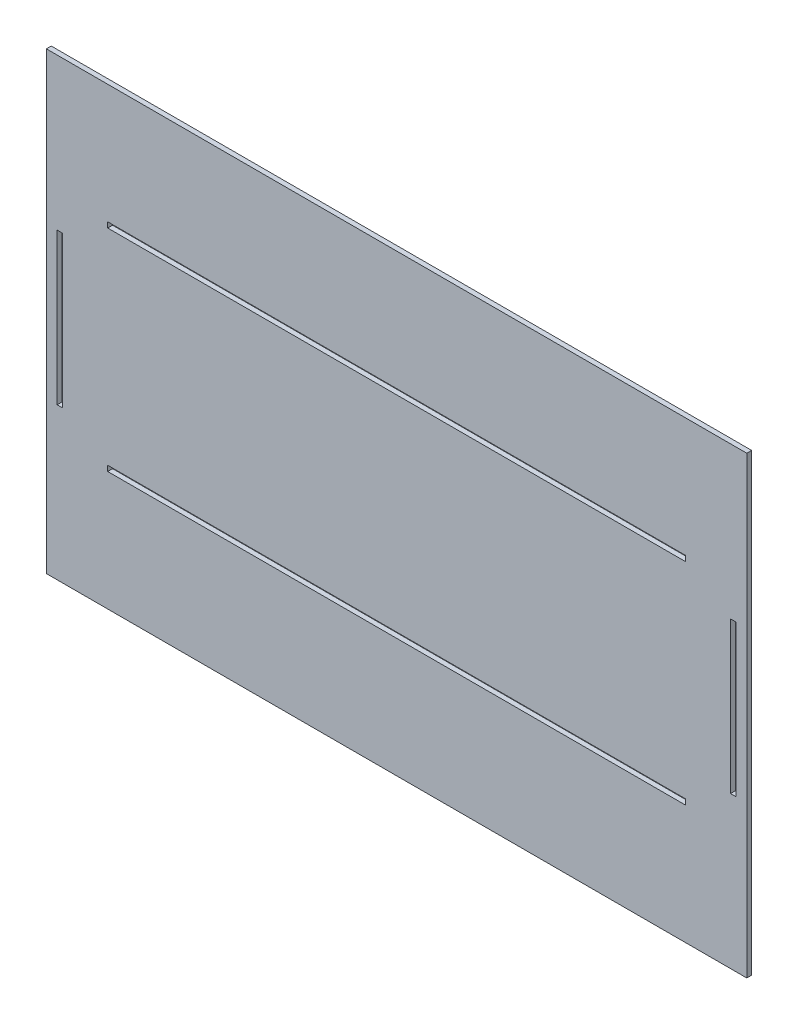
SolidWorks part; units mm, degrees
material "Alloy Steel"
ref_plane "X-Y Datum" through (0, 0, 0) normal (0, 0, 1) x (1, 0, 0)
ref_plane "X-Z Datum" through (0, 0, 0) normal (0, 1, 0) x (1, 0, 0)
ref_plane "Y-Z Datum" through (0, 0, 0) normal (1, 0, 0) x (0, 0, -1)
sketch "Sketch1" plane through (0, 0, 0) normal (0, 0, 1) x (1, 0, 0)
  line L0 (-7.62, -7.62) -> (-7.62, 104.0003)
  line L1 (21.1668, 0) -> (292.2006, 0) construction
  line L2 (0, 12.7) -> (0, 83.6803) construction
  line L3 (21.1668, 96.3803) -> (292.2006, 96.3803) construction
  line L4 (313.3674, 12.7) -> (313.3674, 83.6803) construction
  line L5 (-7.62, 104.0003) -> (320.9874, 104.0003)
  line L6 (320.9874, -7.62) -> (320.9874, 104.0003)
  line L7 (-7.62, -7.62) -> (320.9874, -7.62)
  line L8 (21.1668, 98.9203) -> (21.1668, 96.3803)
  line L10 (0, 83.6803) -> (0, 12.7)
  line L12 (-2.54, 83.6803) -> (-2.54, 12.7)
  line L13 (21.1668, 96.3803) -> (292.2006, 96.3803)
  line L15 (21.1668, 98.9203) -> (292.2006, 98.9203)
  line L18 (313.3674, 83.6803) -> (313.3674, 12.7)
  line L20 (315.9074, 83.6803) -> (315.9074, 12.7)
  line L21 (21.1668, 0) -> (292.2006, 0)
  line L23 (21.1668, -2.54) -> (292.2006, -2.54)
  line L25 (21.1668, 0) -> (21.1668, -2.54)
  line L26 (156.6837, 104.0003) -> (156.6837, 123.0101) construction
  line L27 (0, 96.3803) -> (313.3674, 96.3803) construction
  line L28 (0, 0) -> (313.3674, 0) construction
  line L29 (292.2006, 0) -> (292.2006, -2.54)
  line L30 (292.2006, 98.9203) -> (292.2006, 96.3803)
  line L31 (313.3674, 0) -> (313.3674, 96.3803) construction
  line L32 (0, 83.6803) -> (-2.54, 83.6803)
  line L34 (-2.54, 12.7) -> (0, 12.7)
  line L35 (315.9074, 12.7) -> (313.3674, 12.7)
  line L36 (313.3674, 83.6803) -> (315.9074, 83.6803)
  line L37 (0, 0) -> (0, 96.3803) construction
  dimension "D1" = 7.62
extrude "Boss-Extrude1" add sketch "Sketch1" along normal blind 2.286
sketch "Sketch2" plane through (0, 0, 2.286) normal (0, 0, 1) x (1, 0, 0)
  line L9 (-7.62, 104.0003) -> (320.9874, 104.0003)
  line L10 (-7.62, 104.0003) -> (-7.62, 154.8003)
  line L11 (-7.62, 154.8003) -> (320.9874, 154.8003)
  line L12 (320.9874, 104.0003) -> (320.9874, 154.8003)
  line L13 (-7.62, -7.62) -> (320.9874, -7.62)
  line L14 (-7.62, -7.62) -> (-7.62, -58.42)
  line L15 (-7.62, -58.42) -> (320.9874, -58.42)
  line L16 (320.9874, -7.62) -> (320.9874, -58.42)
extrude "Boss-Extrude2" add sketch "Sketch2" against normal through all
